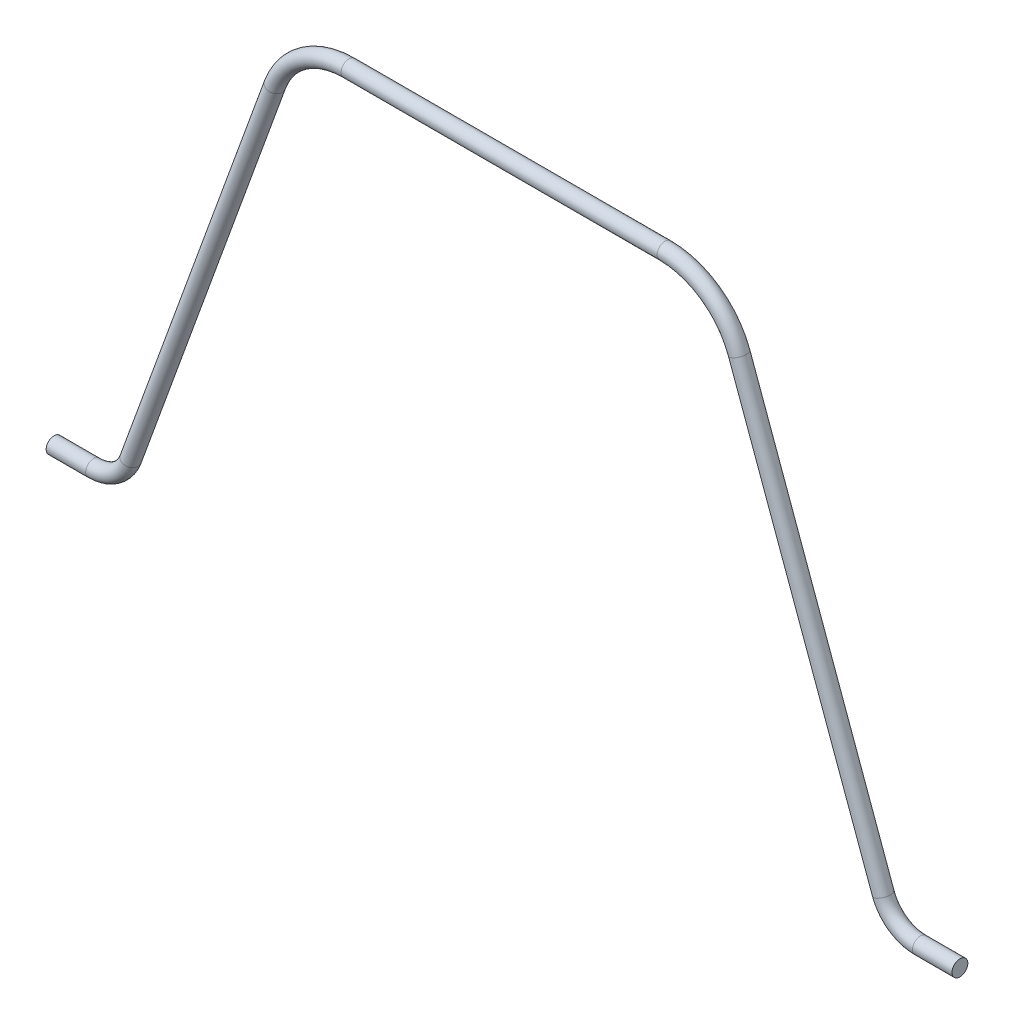
SolidWorks part; units mm, degrees
ref_plane "Front Plane" through (0, 0, 0) normal (0, 0, 1) x (1, 0, 0)
ref_plane "Top Plane" through (0, 0, 0) normal (0, 1, 0) x (1, 0, 0)
ref_plane "Right Plane" through (0, 0, 0) normal (1, 0, 0) x (0, 0, -1)
sketch "Sketch1" plane through (0, 0, 0) normal (1, 0, 0) x (0, 0, -1)
  circle A0 centre (0, 0) radius 2.54
  dimension "D1" = 5.08
sketch "Sketch2" plane through (0, 0, 0) normal (0, 0, 1) x (1, 0, 0)
  line L0 (-50.8, 0) -> (50.8, 0)
  line L1 (74.6682, -16.7127) -> (121.0129, -144.0437)
  line L2 (132.947, -152.4) -> (145.647, -152.4)
  line L3 (0, -0.2794) -> (0, 0.2794) construction
  line L4 (-132.947, -152.4) -> (-145.647, -152.4)
  line L5 (-74.6682, -16.7127) -> (-121.0129, -144.0437)
  arc A0 (50.8, 0) -> (74.6682, -16.7127) centre (50.8, -25.4) cw
  arc A1 (121.0129, -144.0437) -> (132.947, -152.4) centre (132.947, -139.7) ccw
  arc A2 (-121.0129, -144.0437) -> (-132.947, -152.4) centre (-132.947, -139.7) cw
  arc A3 (-50.8, 0) -> (-74.6682, -16.7127) centre (-50.8, -25.4) ccw
  point P7 (131.7896, -152.4)
  point P10 (131.3491, -152.4)
  point P20 (0, 0)
  dimension "D1" = 25.4
  dimension "D5" = 12.7
  dimension "D2" = 50.8
  dimension "D3" = 70
  dimension "D4" = 12.7
  dimension "D6" = 152.4
sweep "Sweep1" add profiles "Sketch1" path "Sketch2"
